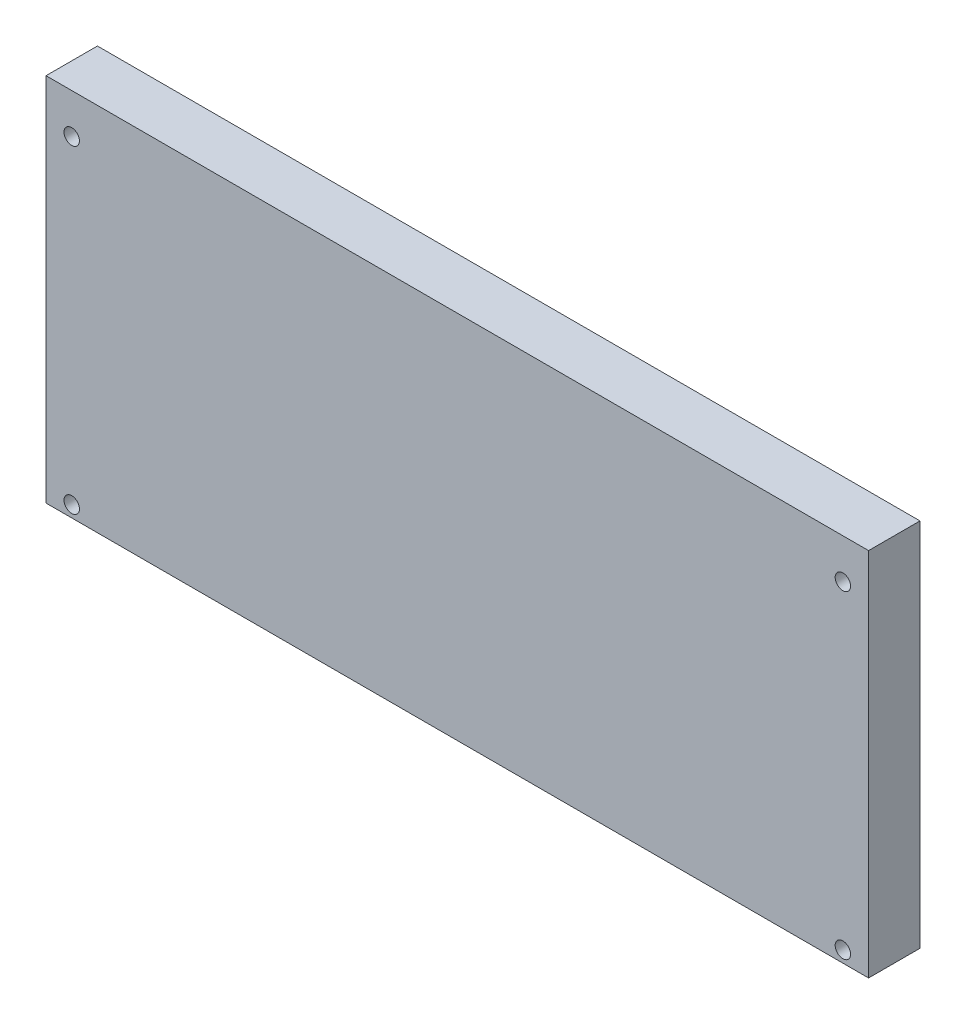
SolidWorks part; units mm, degrees
ref_plane "Front Plane" through (0, 0, 0) normal (0, 0, 1) x (1, 0, 0)
ref_plane "Top Plane" through (0, 0, 0) normal (0, 1, 0) x (1, 0, 0)
ref_plane "Right Plane" through (0, 0, 0) normal (1, 0, 0) x (0, 0, -1)
sketch "Sketch1" plane through (0, 0, 0) normal (0, 0, 1) x (1, 0, 0)
  line L4 (338.532, 24.3821) -> (338.532, 60.3821)
  line L5 (338.532, 24.3821) -> (258.532, 24.3821)
  line L6 (258.532, 24.3821) -> (258.532, 60.3821)
  line L7 (338.532, 60.3821) -> (258.532, 60.3821)
  line L8 (351.6704, 77.2808) -> (245.5332, 77.2808) construction
  line L9 (245.5332, 77.2808) -> (245.5332, 4.2122) construction
  line L10 (351.6704, 4.2122) -> (351.6704, 77.2808) construction
  dimension "D1" = 80
  dimension "D2" = 36
  dimension "D3" = 16.8988
  dimension "D4" = 12.9988
  dimension "D5" = 13.1385
extrude "Boss-Extrude1" add sketch "Sketch1" along normal blind 5
sketch "Sketch2" plane through (0, 0, 0) normal (0, 0, -1) x (-1, 0, 0)
  line L4 (-334.1018, 30.4122) -> (-263.1018, 30.4122)
  line L5 (-334.1018, 54.2122) -> (-334.1018, 30.4122)
  line L6 (-263.1018, 54.2122) -> (-334.1018, 54.2122)
  line L7 (-263.1018, 30.4122) -> (-263.1018, 54.2122)
  line L8 (-334.1018, 30.4122) -> (-263.1018, 30.4122)
  line L9 (-334.1018, 54.2122) -> (-334.1018, 30.4122)
  line L10 (-263.1018, 54.2122) -> (-334.1018, 54.2122)
  line L11 (-263.1018, 30.4122) -> (-263.1018, 54.2122)
  dimension "D1" = 0
extrude "Boss-Extrude2" add sketch "Sketch2" along normal blind 2
sketch "Sketch3" plane through (0, 0, 5) normal (0, 0, 1) x (1, 0, 0)
  circle A1 centre (261.032, 25.5071) radius 0.75
  circle A2 centre (261.032, 25.5071) radius 0.75
  circle A3 centre (336.032, 25.5071) radius 0.75
  circle A4 centre (336.032, 25.5071) radius 0.75
  circle A5 centre (336.032, 56.5071) radius 0.75
  circle A6 centre (336.032, 56.5071) radius 0.75
  circle A7 centre (261.032, 56.5071) radius 0.75
  circle A8 centre (261.032, 56.5071) radius 0.75
  dimension "D1" = 0
  dimension "D2" = 0
  dimension "D3" = 0
  dimension "D4" = 0
extrude "Cut-Extrude1" cut sketch "Sketch3" against normal up to next
